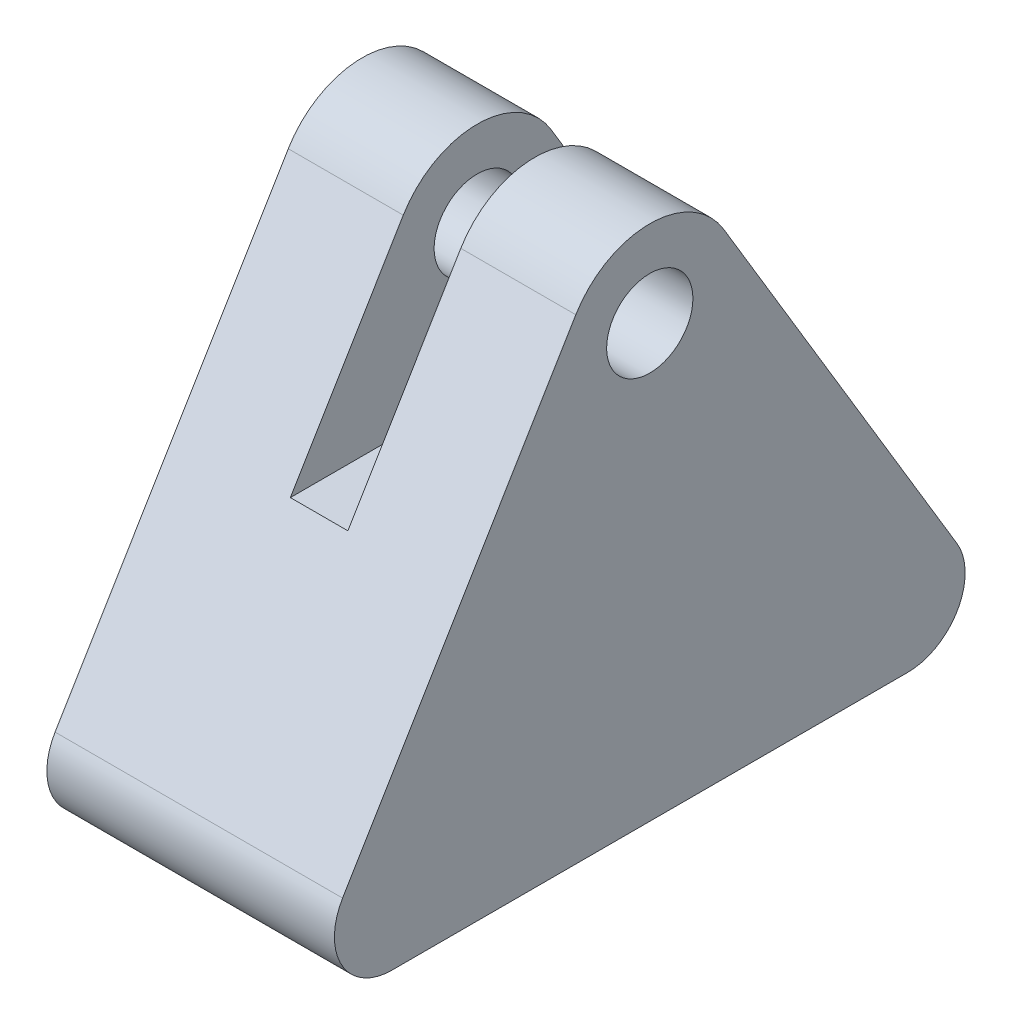
SolidWorks part; units mm, degrees
material "ABS"
ref_plane "Plan de face" through (0, 0, 0) normal (0, 0, 1) x (1, 0, 0)
ref_plane "Plan de dessus" through (0, 0, 0) normal (0, 1, 0) x (1, 0, 0)
ref_plane "Plan de droite" through (0, 0, 0) normal (1, 0, 0) x (0, 0, -1)
sketch "Esquisse1" plane through (0, 0, 0) normal (1, 0, 0) x (0, 0, -1)
  line L0 (2.5724, 1.5437) -> (12.5, -15)
  line L1 (12.5, -15) -> (-12.5, -15)
  line L2 (-12.5, -15) -> (-2.5724, 1.5437)
  line L3 (0, 5.5) -> (0, -5.5) construction
  circle A0 centre (0, 0) radius 1.5
  arc A1 (2.5724, 1.5437) -> (-2.5724, 1.5437) centre (0, 0) ccw
  point P6 (0, -15)
  dimension "D1" = 3
  dimension "D4" = 3
  dimension "D2" = 15
  dimension "D3" = 25
extrude "Boss.-Extru.1" add sketch "Esquisse1" along normal mid plane 10
sketch "Esquisse2" plane through (0, 0, 0) normal (0, 0, 1) x (1, 0, 0)
  line L0 (0, -8.25) -> (0, 8.25) construction
  line L1 (-1, 3) -> (1, 3)
  line L2 (-1, 3) -> (-1, -5)
  line L3 (-1, -5) -> (1, -5)
  line L4 (1, 3) -> (1, -5)
  line L5 (5, 3) -> (-5, 3) construction
  point P4 (0, -5)
  dimension "D1" = 2
  dimension "D2" = 8
extrude "Enlèv. mat.-Extru.1" cut sketch "Esquisse2" against normal through all both and the other way through all
fillet "Congé1" radius 2 2 edges at (0, -15, -12.5) (0, -15, 12.5)
